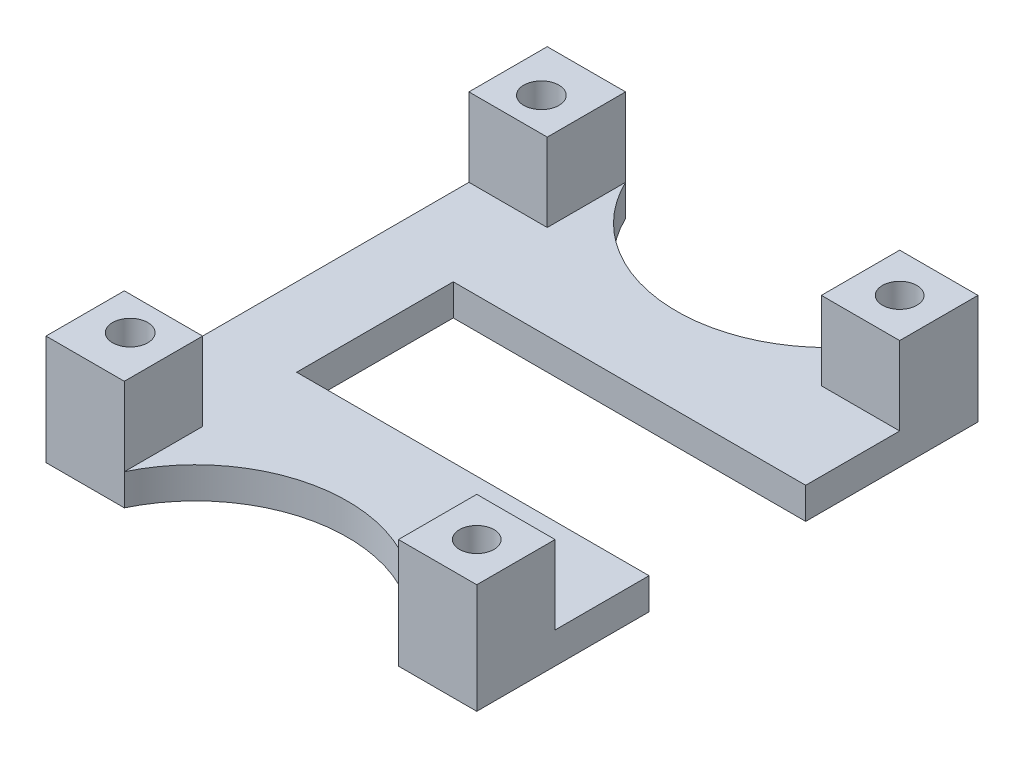
SolidWorks part; units mm, degrees
ref_plane "Front Plane" through (0, 0, 0) normal (0, 0, 1) x (1, 0, 0)
ref_plane "Top Plane" through (0, 0, 0) normal (0, 1, 0) x (1, 0, 0)
ref_plane "Right Plane" through (0, 0, 0) normal (1, 0, 0) x (0, 0, -1)
sketch "Sketch1" plane through (0, 0, 0) normal (0, 1, 0) x (1, 0, 0)
  line L0 (10, 10) -> (10, -10)
  line L1 (0, -20) -> (55, -20)
  line L2 (0, -20) -> (0, 20)
  line L3 (0, 20) -> (55, 20)
  line L4 (55, -20) -> (55, 20) construction
  line L5 (10, -10) -> (45, -10)
  line L6 (45, -10) -> (45, 10) construction
  line L7 (45, 10) -> (10, 10)
  line L8 (45, 10) -> (55, 10)
  line L11 (55, 10) -> (55, 20)
  line L13 (27.5, -20) -> (27.5, -10) construction
  line L14 (27.5, 10) -> (27.5, 20) construction
  line L16 (45, -10) -> (55, -10)
  line L17 (55, -20) -> (55, -10)
  line L18 (55, -20) -> (55, -32)
  line L19 (55, -32) -> (45, -32)
  line L20 (45, -32) -> (45, -20) construction
  line L21 (55, 20) -> (55, 32)
  line L22 (55, 32) -> (45, 32)
  line L23 (45, 32) -> (45, 20) construction
  line L24 (0, -20) -> (0, -32)
  line L25 (0, -32) -> (10, -32)
  line L26 (10, -32) -> (10, -20) construction
  line L27 (0, 20) -> (0, 32)
  line L28 (0, 32) -> (10, 32)
  line L29 (10, 32) -> (10, 20) construction
  line L30 (-55, 0) -> (55, 0) construction
  line L31 (0, 0) -> (55, 0) construction
  arc A26 (45, -32) -> (10, -32) centre (27.5, -40.4205) ccw
  arc A27 (10, 32) -> (45, 32) centre (27.5, 40.4205) ccw
  circle A46 centre (50, 27) radius 2.2
  circle A47 centre (50, -27) radius 2.2
  circle A49 centre (5, 26.25) radius 2.2479 construction
  circle A50 centre (5, 26.25) radius 2.2479
  circle A51 centre (5, -26.25) radius 2.2479 construction
  circle A52 centre (5, -26.25) radius 2.2479
  point P33 (27.5, 21)
  point P34 (27.5, -21)
  point P39 (0, 0)
  dimension "D18" = 4.4
  dimension "D19" = 4.4
  dimension "D1" = 40
  dimension "D2" = 55
  dimension "D3" = 10
  dimension "D22" = 10
  dimension "D23" = 10
  dimension "D24" = 10
  dimension "D13" = 5
  dimension "D16" = 5
  dimension "D7" = 10
  dimension "D10" = 12
  dimension "D11" = 12
  dimension "D12" = 10
  dimension "D9" = 5
  dimension "D14" = 5
  dimension "D15" = 12
  dimension "D17" = 10
  dimension "D20" = 10
  dimension "D21" = 12
  dimension "D27" = 1
  dimension "D28" = 1
extrude "Extrude-Body" add sketch "Sketch1" along normal blind 4
sketch "Sketch5" plane through (0, 4, 0) normal (0, 1, 0) x (1, 0, 0)
  line L9 (45, -22) -> (55, -22)
  line L21 (55, -22) -> (55, -32)
  line L36 (55, -32) -> (45, -32)
  line L37 (45, -32) -> (45, -22)
  line L38 (55, 22) -> (55, 32)
  line L39 (55, 32) -> (45, 32)
  line L41 (45, 32) -> (45, 22)
  line L42 (45, 22) -> (55, 22)
  line L43 (10, 22) -> (10, 32)
  line L44 (10, 32) -> (0, 32)
  line L46 (0, 32) -> (0, 22)
  line L47 (0, -32) -> (0, 32) construction
  line L48 (0, 22) -> (10, 22)
  line L49 (10, -22) -> (0, -22)
  line L50 (0, -22) -> (0, -32)
  line L51 (0, -32) -> (10, -32)
  line L52 (10, -32) -> (10, -22)
  circle A0 centre (50, 27) radius 2.2
  circle A3 centre (50, -27) radius 2.2
  circle A11 centre (50, 27) radius 2.2 construction
  circle A12 centre (50, -27) radius 2.2 construction
  circle A13 centre (5, -26.25) radius 2.2479 construction
  circle A14 centre (5, -26.25) radius 2.2479
  circle A15 centre (5, 26.25) radius 2.2479 construction
  circle A16 centre (5, 26.25) radius 2.2479
  dimension "D1" = 10
  dimension "D2" = 10
  dimension "D3" = 10
  dimension "D4" = 10
  dimension "D5" = 10
  dimension "D6" = 10
  dimension "D7" = 10
  dimension "D8" = 10
extrude "Extrude-Legs" add sketch "Sketch5" along normal blind 10
sketch "Sketch6" plane through (0, 0, 0) normal (0, -1, 0) x (1, 0, 0)
  circle A3 centre (50, 27) radius 4.215
  circle A5 centre (50, -27) radius 4.215
  dimension "D1" = 8.43
  dimension "D3" = 8.43
extrude "Cut-Bolt Head Insets" cut sketch "Sketch6" against normal blind 2.5
equation "\"boltdiameter\"=4.4"
equation "\"D18@Sketch1\"=\"boltdiameter\""
equation "\"D19@Sketch1\"=\"boltdiameter\""
equation "\"boltfacediameter\"=7"
equation "\"insetNutFlat\"=8.4"
equation "\"screwInset\"=8.43"
equation "\"D1@Sketch6\"=\"screwInset\""
equation "\"D3@Sketch6\"=\"screwInset\""
equation "\"slotLength\"=80"
